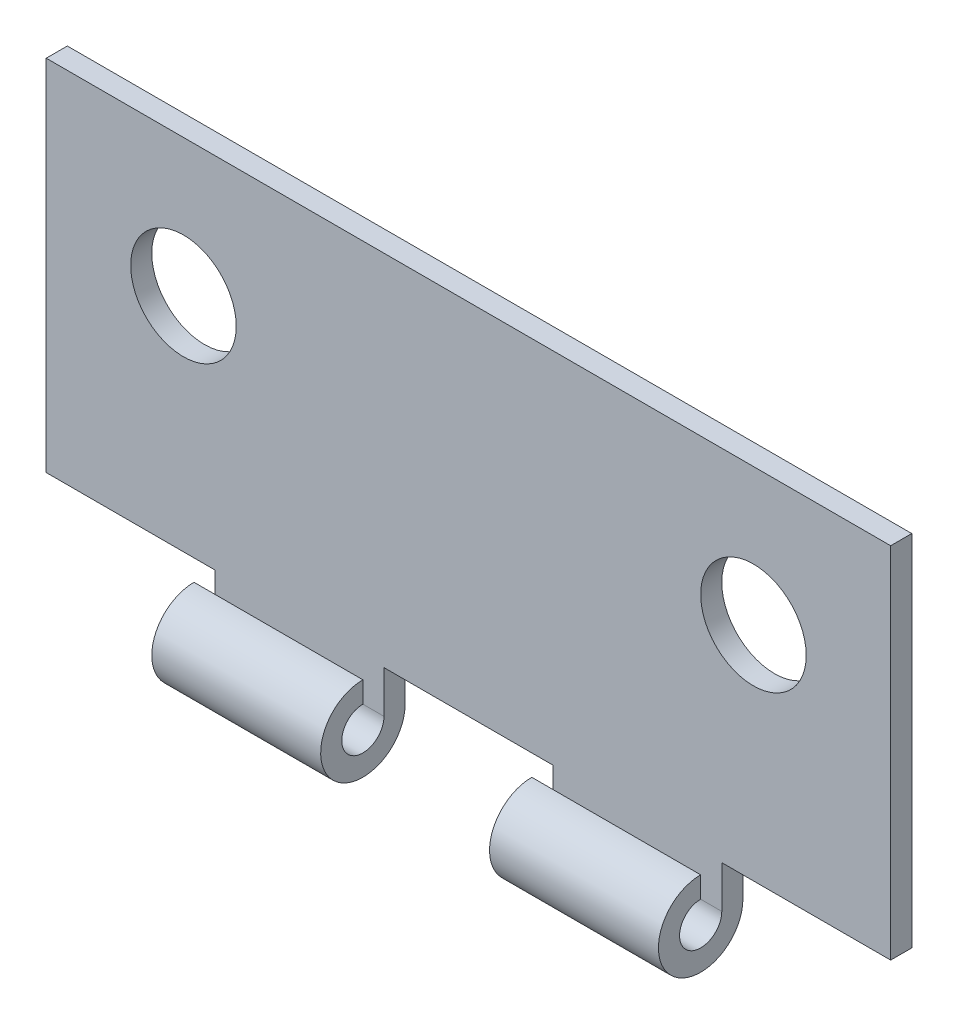
SolidWorks part; units mm, degrees
ref_plane "Plan de face" through (0, 0, 0) normal (0, 0, 1) x (1, 0, 0)
ref_plane "Plan de dessus" through (0, 0, 0) normal (0, 1, 0) x (1, 0, 0)
ref_plane "Plan de droite" through (0, 0, 0) normal (1, 0, 0) x (0, 0, -1)
sketch "Esquisse1" plane through (0, 0, 0) normal (0, 0, 1) x (1, 0, 0)
  line L1 (0, 0) -> (40, 0)
  line L2 (0, 0) -> (0, 17)
  line L3 (0, 17) -> (40, 17)
  line L4 (40, 0) -> (40, 17)
  dimension "D1" = 17
  dimension "D2" = 40
extrude "Boss.-Extru.1" add sketch "Esquisse1" along normal blind 1
sketch "Esquisse2" plane through (0, 0, 1) normal (0, 0, 1) x (1, 0, 0)
  line L0 (40, 17) -> (0, 17) construction
  line L1 (0, 17) -> (0, 0) construction
  line L2 (40, 0) -> (40, 17) construction
  circle A0 centre (6.5, 10.5) radius 2.5
  circle A1 centre (33.5, 10.5) radius 2.5
  point P8 (0, 0)
  dimension "D1" = 5
  dimension "D2" = 6.5
  dimension "D3" = 6.5
  dimension "D4" = 6.5
extrude "Enlèv. mat.-Extru.1" cut sketch "Esquisse2" against normal up to next
ref_plane "Plan1" through (8, 0, 0) normal (-1, 0, 0) x (0, 0, 1)
sketch "Esquisse3" plane through (8, 0, 0) normal (-1, 0, 0) x (0, 0, 1)
  line L0 (0, 0) -> (0, -2)
  line L1 (2, 0) -> (2, -1)
  line L2 (1, -2) -> (1, 0)
  line L3 (0, 0) -> (1, 0)
  arc A0 (0, -2) -> (2, 0) centre (2, -2) ccw
  arc A1 (2, -1) -> (1, -2) centre (2, -2) cw
  point P3 (0, 0)
  dimension "D1" = 2
  dimension "D2" = 1
  dimension "D3" = 1
extrude "Boss.-Extru.2" add sketch "Esquisse3" against normal blind 8
ref_plane "Plan2" through (20, 0, 0) normal (-1, 0, 0) x (0, 0, 1)
mirror "Symétrie1" about plane through (20, 0, 0) normal (-1, 0, 0) of "Boss.-Extru.2"
